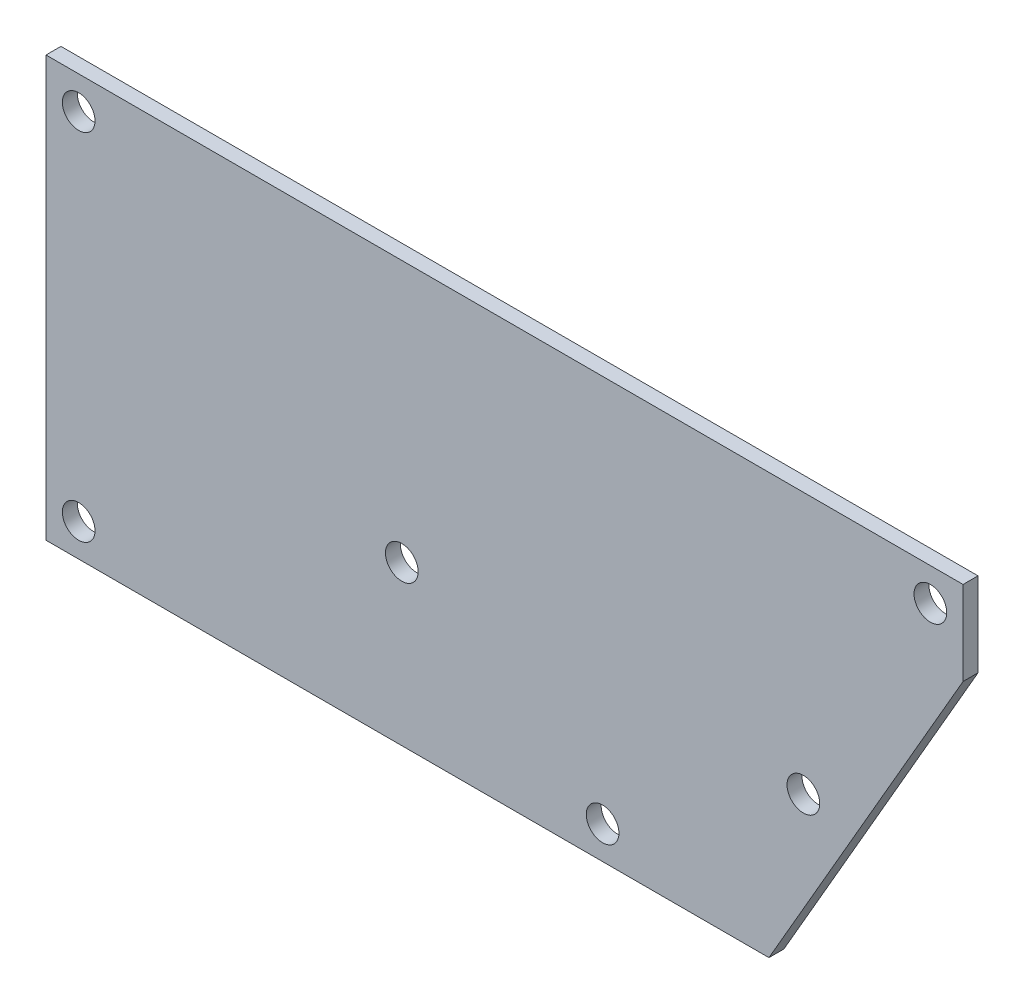
SolidWorks part; units mm, degrees
material "A-Glass Fiber"
ref_plane "Front Plane" through (0, 0, 0) normal (0, 0, 1) x (1, 0, 0)
ref_plane "Top Plane" through (0, 0, 0) normal (0, 1, 0) x (1, 0, 0)
ref_plane "Right Plane" through (0, 0, 0) normal (1, 0, 0) x (0, 0, -1)
sketch "PCB"
  line L0 (-49.098, 0) -> (49.098, 0) construction
  line L1 (-49.098, 15) -> (49.098, 15) construction
  line L2 (-49.098, 15) -> (-49.098, -24)
  line L3 (-49.098, -24) -> (28.3134, -24)
  line L4 (49.098, 21) -> (49.098, 12)
  line L6 (49.098, 12) -> (28.3134, -24)
  line L7 (0, 15) -> (0, -24) construction
  line L8 (-49.098, 15) -> (-49.098, 21)
  line L9 (-49.098, 21) -> (49.098, 21)
  line L10 (49.098, 21) -> (49.098, 15) construction
  line L11 (45.598, 17.5) -> (45.598, 14) construction
  line L12 (0, 21) -> (0, 0) construction
  line L13 (10.5, -7) -> (10.5, -20.5) construction
  line L18 (-11, -7) -> (32, -7) construction
  circle A3 centre (45.598, 17.5) radius 1.75
  circle A6 centre (10.5, -20.5) radius 1.75
  circle A8 centre (45.598, 17.5) radius 3.5 construction
  circle A9 centre (10.5, -20.5) radius 3.5 construction
  circle A10 centre (32, -7) radius 1.75
  circle A11 centre (32, -7) radius 3.5 construction
  circle A12 centre (-11, -7) radius 1.75
  circle A13 centre (-11, -7) radius 3.5 construction
  circle A14 centre (-45.598, 17.5) radius 3.5 construction
  circle A15 centre (-45.598, 17.5) radius 1.75
  circle A16 centre (-45.598, -20.5) radius 3.5 construction
  circle A17 centre (-45.598, -20.5) radius 1.75
  point P0 (0, 0)
  point P27 (10.5, -7)
  dimension "D5" = 3.5
  dimension "D6" = 7
  dimension "D1" = 15
  dimension "D2" = 98.196
  dimension "D3" = 7
  dimension "D4" = 24
  dimension "D8" = 60
  dimension "D9" = 9
  dimension "D10" = 6
  dimension "D11" = 11
  dimension "D13" = 43
extrude "Boss-Extrude1" add sketch "PCB" along normal blind 1.6
ref_plane "PCB Top" through (0, 0, 1.6) normal (0, 0, 1) x (1, 0, 0)
